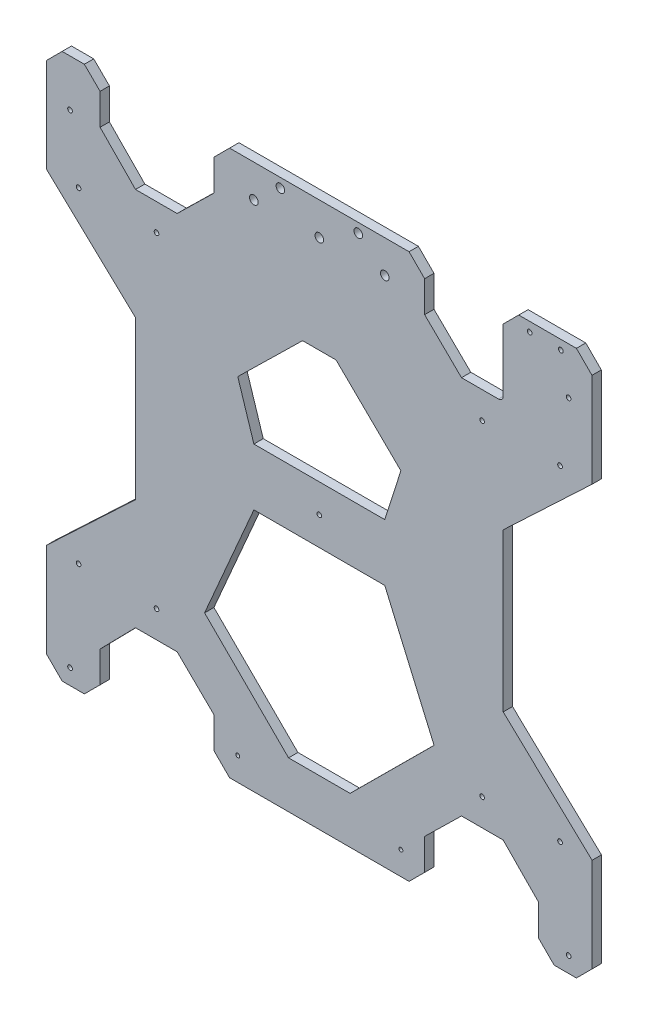
SolidWorks part; units mm, degrees
material "7050-T73510"
ref_plane "Piano frontale" through (0, 0, 0) normal (0, 0, 1) x (1, 0, 0)
ref_plane "Piano superiore" through (0, 0, 0) normal (0, 1, 0) x (1, 0, 0)
ref_plane "Piano destro" through (0, 0, 0) normal (1, 0, 0) x (0, 0, -1)
sketch "Schizzo13" plane through (0, 0, 0) normal (0, 0, 1) x (1, 0, 0)
  line L0 (175, 350) -> (175, 0) construction
  line L1 (9.9192, 0) -> (24.2012, 0)
  line L2 (-0.0808, 279.5) -> (57, 225.6111)
  line L3 (217, 193.2869) -> (227.343, 225.6111)
  line L4 (133, 193.2869) -> (217, 193.2869)
  line L5 (350, 175) -> (0, 175) construction
  line L6 (-60.1887, 10) -> (461.2643, 10) construction
  line L7 (279.5, 279.5) -> (279.5, 175) construction
  line L8 (-12.961, 344) -> (386.8832, 344) construction
  line L9 (-12.961, 329) -> (386.8832, 329) construction
  line L10 (185.7509, 30) -> (185.7509, 0) construction
  line L11 (279.5, 70.5) -> (175, 70.5) construction
  line L12 (70.5, 70.5) -> (175, 70.5) construction
  line L13 (185.7509, 15) -> (120.1229, 15) construction
  line L15 (70.5, 279.5) -> (169.5845, 279.5) construction
  line L16 (175, 279.5) -> (329.5, 279.5) construction
  line L17 (329.5, 70.5) -> (329.5, 279.5) construction
  line L18 (20.5, 70.5) -> (329.5, 70.5) construction
  line L19 (20.5, 70.5) -> (20.5, 279.5) construction
  line L20 (175, 279.5) -> (20.5, 279.5) construction
  line L21 (15, -40.9714) -> (15, 408.5301) construction
  line L22 (335, -40.9714) -> (335, 408.5301) construction
  line L23 (-12.961, 320) -> (386.8832, 320) construction
  line L24 (9.9192, 0) -> (-0.0808, 10)
  line L25 (340, 0) -> (350, 10)
  line L26 (107.4046, 340) -> (107.4046, 320)
  line L27 (107.4046, 320) -> (83.7454, 296.8073)
  line L28 (70.5, 279.5) -> (20.5, 279.5) construction
  line L29 (57.0174, 296.8073) -> (34.282, 320)
  line L30 (83.7454, 296.8073) -> (57.0174, 296.8073)
  line L31 (34.282, 320) -> (34.282, 340)
  line L32 (24.2012, 350) -> (9.9192, 350)
  line L33 (133, 193.2869) -> (122.657, 225.6111)
  line L35 (164.2491, 266.3832) -> (185.7509, 266.3832)
  line L36 (122.657, 225.6111) -> (164.2491, 266.3832)
  line L37 (57, 225.6111) -> (57, 175)
  line L38 (227.343, 225.6111) -> (185.7509, 266.3832)
  line L39 (293, 225.6111) -> (293, 124.3889)
  line L40 (350.0808, 279.5) -> (293, 225.6111)
  line L44 (292.9826, 299.8073) -> (292.9826, 340)
  line L46 (117.4046, 0) -> (232.5954, 0)
  line L47 (266.2546, 296.8073) -> (289.9826, 296.8073)
  line L48 (242.5954, 320) -> (266.2546, 296.8073)
  line L49 (242.5954, 340) -> (242.5954, 320)
  line L50 (350.0808, 70.5) -> (293, 124.3889)
  line L53 (350, 10) -> (350.0808, 70.5)
  line L55 (315.718, 30) -> (315.718, 10)
  line L56 (292.9826, 53.1927) -> (315.718, 30)
  line L57 (266.2546, 53.1927) -> (292.9826, 53.1927)
  line L58 (242.5954, 30) -> (266.2546, 53.1927)
  line L59 (242.5954, 10) -> (242.5954, 30)
  line L60 (107.4046, 10) -> (107.4046, 30)
  line L61 (107.4046, 30) -> (83.7454, 53.1927)
  line L62 (83.7454, 53.1927) -> (57.0174, 53.1927)
  line L63 (57.0174, 53.1927) -> (34.282, 30)
  line L64 (34.282, 30) -> (34.2012, 10)
  line L66 (-0.0808, 10) -> (-0.0808, 70.5)
  line L69 (-0.0808, 70.5) -> (57, 124.3889)
  line L70 (57, 124.3889) -> (57, 175)
  line L71 (-0.0808, 279.5) -> (-0.0808, 340)
  line L72 (117.4046, 350) -> (232.5954, 350)
  line L73 (302.9826, 350) -> (340, 350)
  line L74 (350.0808, 279.5) -> (350, 340)
  line L75 (325.718, 0) -> (340, 0)
  line L76 (24.2012, 0) -> (34.2012, 10)
  line L77 (117.4046, 0) -> (107.4046, 10)
  line L78 (232.5954, 0) -> (242.5954, 10)
  line L79 (315.718, 10) -> (325.718, 0)
  line L80 (9.9192, 350) -> (-0.0808, 340)
  line L81 (24.2012, 350) -> (34.282, 340)
  line L82 (107.4046, 340) -> (117.4046, 350)
  line L83 (232.5954, 350) -> (242.5954, 340)
  line L84 (292.9826, 340) -> (302.9826, 350)
  line L85 (340, 350) -> (350, 340)
  line L86 (133, 156.7131) -> (101.3482, 83.6168)
  line L87 (101.3482, 83.6168) -> (155.2542, 30)
  line L88 (155.2542, 30) -> (194.7458, 30)
  line L89 (133, 156.7131) -> (217, 156.7131)
  line L90 (248.6518, 83.6168) -> (194.7458, 30)
  line L91 (217, 156.7131) -> (248.6518, 83.6168)
  circle A0 centre (15, 320) radius 1.5
  circle A1 centre (20.5, 279.5) radius 1.5
  circle A2 centre (70.5, 279.5) radius 1.5
  circle A3 centre (175, 175) radius 1.5
  arc A4 (289.9826, 296.8073) -> (292.9826, 299.8073) centre (289.9826, 299.8073) ccw
  circle A5 centre (20.5, 70.5) radius 1.5
  circle A6 centre (200, 344) radius 2.75
  circle A7 centre (150, 344) radius 2.75
  circle A8 centre (175, 329) radius 2.75
  circle A9 centre (217, 329) radius 2.75
  circle A10 centre (133, 329) radius 2.75
  circle A11 centre (70.5, 70.5) radius 1.5
  circle A12 centre (279.5, 70.5) radius 1.5
  circle A13 centre (329.5, 70.5) radius 1.5
  circle A14 centre (335, 10) radius 1.5
  circle A15 centre (15, 10) radius 1.5
  circle A16 centre (279.5, 279.5) radius 1.5
  circle A17 centre (329.5, 279.5) radius 1.5
  circle A18 centre (335, 320) radius 1.5
  circle A19 centre (310, 344) radius 1.5
  circle A20 centre (330, 344) radius 1.5
  circle A21 centre (122.657, 15) radius 1.25
  circle A22 centre (227.343, 15) radius 1.25
  point P7 (175, 175)
  point P25 (175, 344)
  point P30 (175, 329)
  point P41 (175, 175)
  point P43 (329.5, 175)
  point P46 (15, 320)
  point P54 (335, 320)
  point P55 (335, 10)
  point P56 (15, 10)
  point P57 (15, 320)
  point P58 (335, 320)
  point P59 (15, 10)
  point P60 (335, 10)
  point P93 (292.9826, 296.8073)
  point P155 (175, 156.7131)
  point P156 (175, 30)
  dimension "D5" = 42
  dimension "D6" = 5.5
  dimension "D7" = 25
  dimension "D8" = 15
  dimension "D10" = 154.5
  dimension "D3" = 104.5
  dimension "D17" = 20
  dimension "D2" = 3
  dimension "D14" = 2.5
  dimension "D4" = 104.5
  dimension "D9" = 175
  dimension "D11" = 104.5
  dimension "D12" = 279.5
  dimension "D13" = 104.5
  dimension "D15" = 310
  dimension "D16" = 320
extrude "Estrusione-Estrusione2" add sketch "Schizzo13" against normal blind 6
sketch "Schizzo14" plane through (0, 0, 0) normal (0, 0, 1) x (1, 0, 0)
  line L0 (350, 350) -> (0, 350)
  line L1 (232.5954, 350) -> (117.4046, 350) construction
  line L2 (0, 350) -> (0, 0)
  line L3 (0, 0) -> (350, 0)
  line L4 (117.4046, 0) -> (232.5954, 0) construction
  line L5 (175, 350) -> (175, 0) construction
  line L6 (350, 350) -> (350, 0)
  line L7 (248.6518, 83.6168) -> (101.3482, 83.6168) construction
  line L8 (227.343, 225.6111) -> (122.657, 225.6111) construction
  point P13 (201.063, 225.6111)
  point P14 (208.5822, 83.6168)
  point P17 (141.4178, 83.6168)
  point P18 (148.937, 225.6111)
sketch "Schizzo15" plane through (0, 0, 0) normal (0, 0, 1) x (1, 0, 0)
  text T0 "HackerBot" font "Lobster 1.4" height 14
